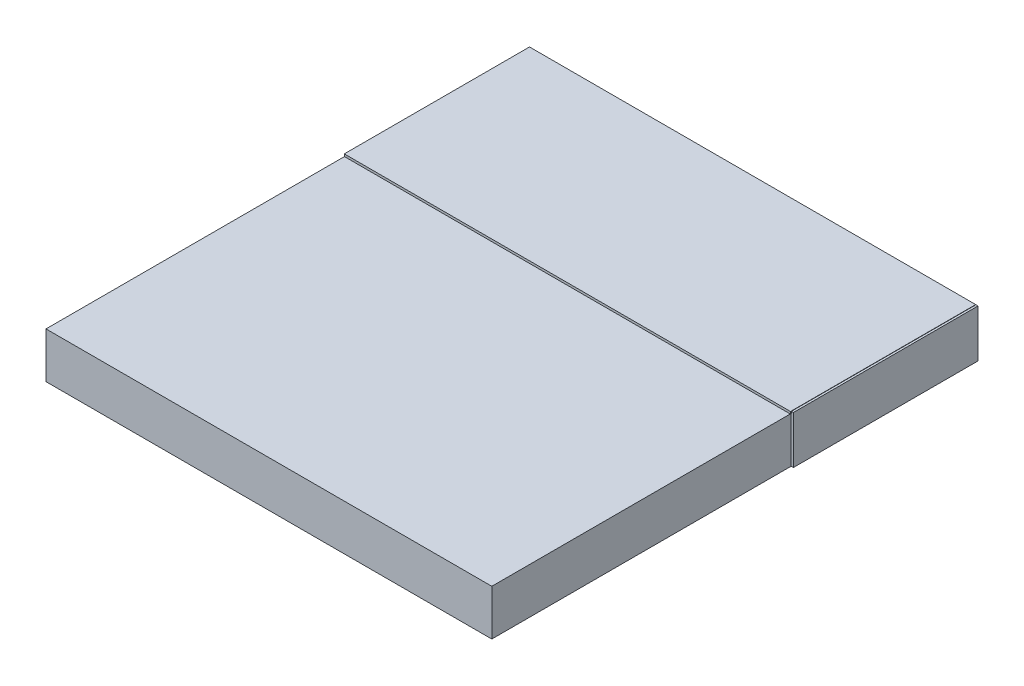
SolidWorks part; units mm, degrees
ref_plane "Front Plane" through (0, 0, 0) normal (0, 0, 1) x (1, 0, 0)
ref_plane "Top Plane" through (0, 0, 0) normal (0, 1, 0) x (1, 0, 0)
ref_plane "Right Plane" through (0, 0, 0) normal (1, 0, 0) x (0, 0, -1)
sketch "Sketch1" plane through (0, 0, 0) normal (0, 1, 0) x (1, 0, 0)
  line L1 (-9.7514, 10.5858) -> (9.7514, 10.5858)
  line L2 (-9.7514, 10.5858) -> (-9.7514, -10.5858)
  line L3 (-9.7514, -10.5858) -> (9.7514, -10.5858)
  line L4 (9.7514, 10.5858) -> (9.7514, -10.5858)
  line L5 (-9.7514, 10.5858) -> (9.7514, -10.5858) construction
  line L6 (-9.7514, -10.5858) -> (9.7514, 10.5858) construction
  point P0 (0, 0)
extrude "Boss-Extrude1" add sketch "Sketch1" along normal blind 2
sketch "Sketch2" plane through (0, 2, 0) normal (0, 1, 0) x (1, 0, 0)
  line L1 (-9.7578, 10.5725) -> (9.7627, 10.5725)
  line L2 (-9.7578, 10.5725) -> (-9.7578, 2.4704)
  line L3 (-9.7578, 2.4704) -> (9.7627, 2.4704)
  line L4 (9.7627, 10.5725) -> (9.7627, 2.4704)
  line L5 (-9.7578, 10.5725) -> (9.7627, 2.4704) construction
  line L6 (-9.7578, 2.4704) -> (9.7627, 10.5725) construction
  point P0 (0.0024, 6.5214)
extrude "Boss-Extrude2" add sketch "Sketch2" along normal blind 0.1
sketch "Sketch3" plane through (9.7514, 0, 0) normal (1, 0, 0) x (0, 0, -1)
  line L1 (2.5097, 2.0858) -> (10.5843, 2.0858)
  line L2 (2.5097, 2.0858) -> (2.5097, 0.0012)
  line L3 (2.5097, 0.0012) -> (10.5843, 0.0012)
  line L4 (10.5843, 2.0858) -> (10.5843, 0.0012)
  line L5 (2.5097, 2.0858) -> (10.5843, 0.0012) construction
  line L6 (2.5097, 0.0012) -> (10.5843, 2.0858) construction
  point P0 (6.547, 1.0435)
extrude "Boss-Extrude3" add sketch "Sketch3" along normal blind 0.1
